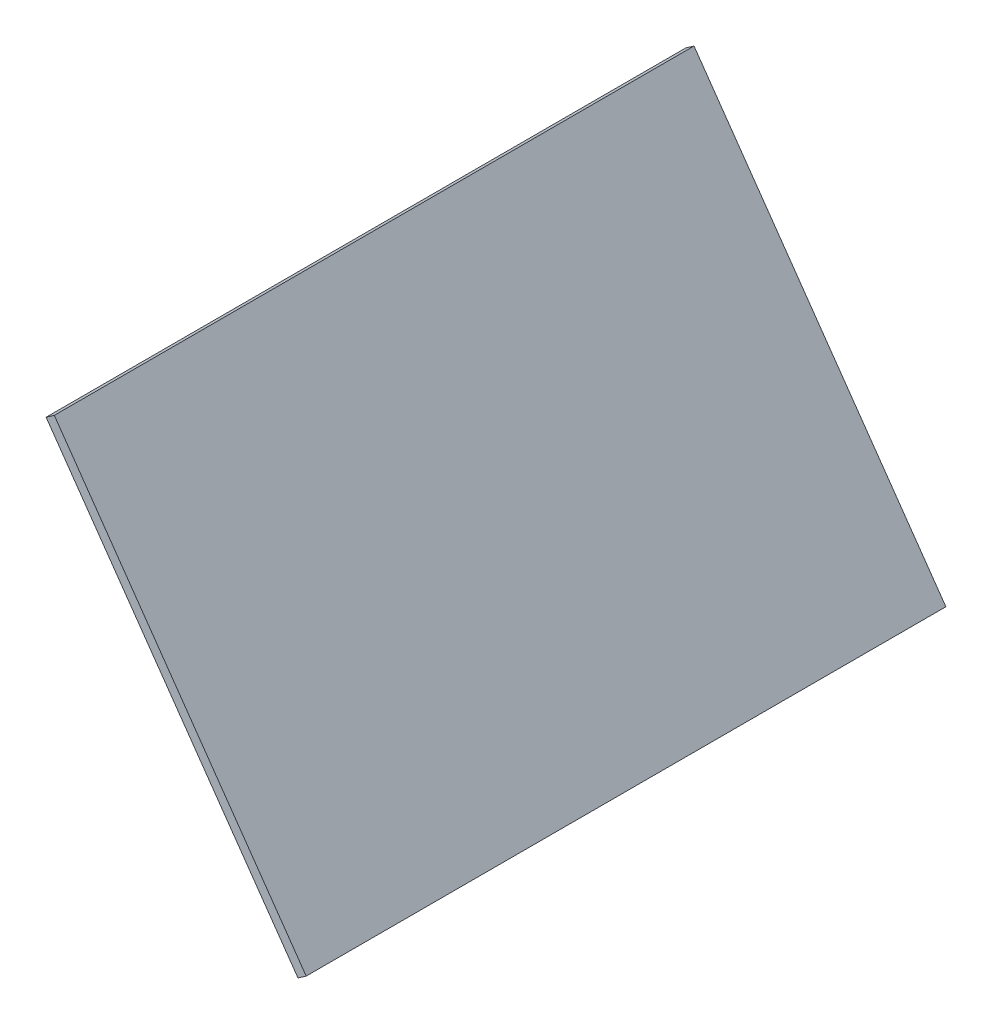
SolidWorks part; units mm, degrees
ref_plane "Front" through (0, 0, 0) normal (0, 0, 1) x (1, 0, 0)
ref_plane "Top" through (0, 0, 0) normal (0, 1, 0) x (1, 0, 0)
ref_plane "Right" through (0, 0, 0) normal (1, 0, 0) x (0, 0, -1)
sketch "Sketch1" plane through (0, 0, 0) normal (0, 0, 1) x (1, 0, 0)
  line L0 (0, 0) -> (-10.16, 0) construction
  line L1 (-10.16, 0) -> (-50.8, 58.0399) construction
  line L2 (-50.8, 58.0399) -> (0, 58.0399) construction
  line L3 (0, 58.0399) -> (0, 0) construction
  line L4 (-10.7976, 0.9106) -> (-12.098, 0)
  line L5 (-10.16, 0) -> (-27.8867, 0) construction
  line L6 (-50.8, 58.0399) -> (-52.1004, 57.1294)
  line L7 (-52.1004, 57.1294) -> (-12.098, 0)
  line L8 (-50.8, 58.0399) -> (-10.7976, 0.9106)
  dimension "D1" = 50.8
  dimension "D2" = 10.16
  dimension "D3" = 55
  dimension "D4" = 1.5875
extrude "Boss-Extrude1" add sketch "Sketch1" along normal blind 101.6
